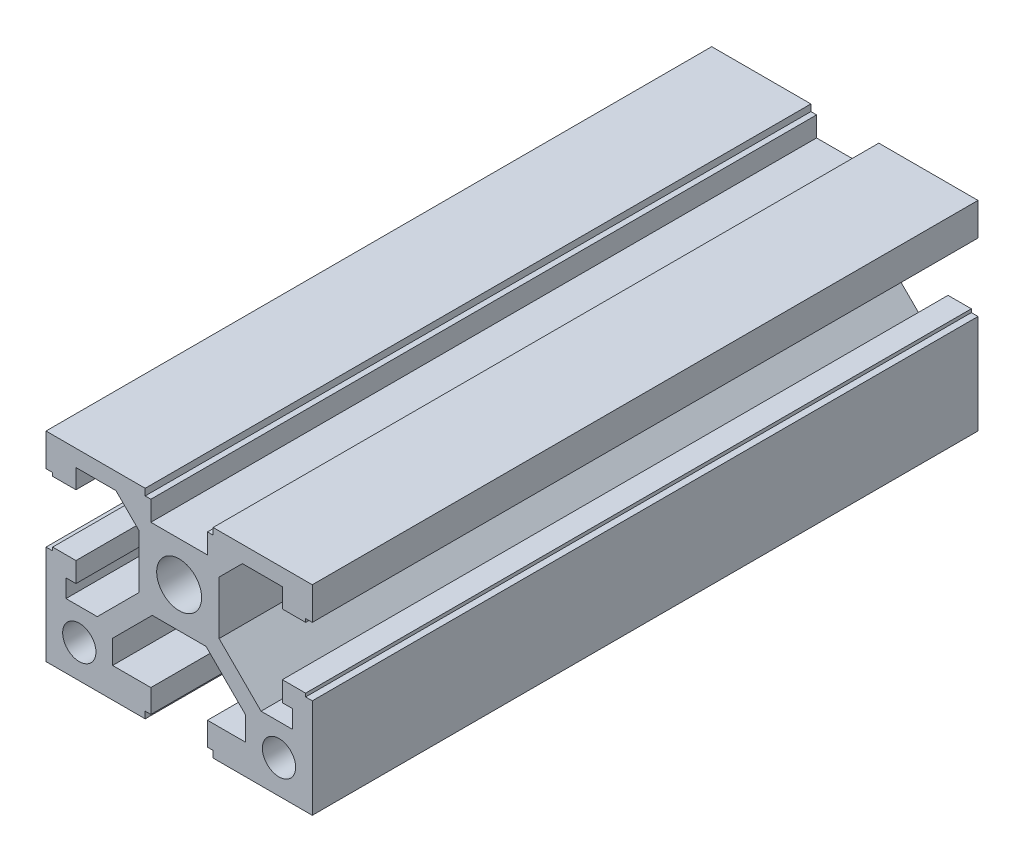
SolidWorks part; units mm, degrees
ref_plane "前视基准面" through (0, 0, 0) normal (0, 0, 1) x (1, 0, 0)
ref_plane "上视基准面" through (0, 0, 0) normal (0, 1, 0) x (1, 0, 0)
ref_plane "右视基准面" through (0, 0, 0) normal (1, 0, 0) x (0, 0, -1)
sketch "草图1" plane through (0, 0, 0) normal (0, 0, 1) x (1, 0, 0)
  line L0 (20, 41.4177) -> (20, -4.8401) construction
  line L1 (0, 0) -> (14.9, 0)
  line L2 (0, 0) -> (0, 14.9)
  line L3 (0, 30) -> (14.9, 30)
  line L4 (40, 0) -> (40, 14.9)
  line L5 (0, 25.1) -> (0, 30)
  line L6 (14.9, 30) -> (14.9, 29)
  line L7 (14.9, 29) -> (15.75, 29)
  line L8 (25.1, 30) -> (25.1, 29)
  line L9 (25.1, 30) -> (40, 30)
  line L10 (15.75, 29) -> (15.75, 26)
  line L11 (15.75, 26) -> (24.25, 26)
  line L12 (24.25, 29) -> (24.25, 26)
  line L13 (-17.1816, 20) -> (59.6344, 20) construction
  line L14 (24.25, 29) -> (25.1, 29)
  line L15 (0, 25.1) -> (1, 25.1)
  line L16 (4.5, 15.4) -> (4.5, 12.4)
  line L17 (0, 14.9) -> (1, 14.9)
  line L18 (1, 25.1) -> (1, 24.6)
  line L19 (1, 24.6) -> (4.5, 24.6)
  line L20 (10.5, 27.5) -> (14, 24)
  line L21 (1, 15.4) -> (4.5, 15.4)
  line L22 (14, 24) -> (14, 16)
  line L23 (4.5, 27.5) -> (10.5, 27.5)
  line L24 (4.5, 27.5) -> (4.5, 24.6)
  line L25 (4.5, 12.4) -> (3, 12.4)
  line L26 (32.3, 9.7) -> (32.3031, 9.7306)
  line L27 (1, 15.4) -> (1, 14.9)
  line L28 (14, 16) -> (7.7, 9.7)
  line L29 (3, 12.4) -> (3, 9.7)
  line L30 (3, 9.7) -> (7.7, 9.7)
  line L31 (7.7, 9.7) -> (7.6969, 9.7306)
  line L32 (37, 9.7) -> (32.3, 9.7)
  line L33 (37, 12.4) -> (37, 9.7)
  line L34 (26, 16) -> (32.3, 9.7)
  line L35 (39, 15.4) -> (39, 14.9)
  line L36 (35.5, 12.4) -> (37, 12.4)
  line L37 (35.5, 27.5) -> (35.5, 24.6)
  line L38 (35.5, 27.5) -> (29.5, 27.5)
  line L39 (26, 24) -> (26, 16)
  line L40 (39, 15.4) -> (35.5, 15.4)
  line L41 (29.5, 27.5) -> (26, 24)
  line L42 (39, 24.6) -> (35.5, 24.6)
  line L43 (39, 25.1) -> (39, 24.6)
  line L44 (40, 14.9) -> (39, 14.9)
  line L45 (35.5, 15.4) -> (35.5, 12.4)
  line L46 (40, 25.1) -> (39, 25.1)
  line L47 (40, 25.1) -> (40, 30)
  line L48 (25.1, 0) -> (40, 0)
  line L49 (30, 8.0402) -> (24.0402, 14)
  line L50 (14.9, 0) -> (14.9, 1)
  line L51 (14.9, 1) -> (15.75, 1)
  line L52 (30, 4.5) -> (30, 8.0402)
  line L53 (15.75, 4.5) -> (10, 4.5)
  line L54 (15.75, 1) -> (15.75, 4.5)
  line L55 (24.25, 1) -> (24.25, 4.5)
  line L56 (24.25, 4.5) -> (30, 4.5)
  line L57 (10, 4.5) -> (10, 8.0402)
  line L58 (10, 8.0402) -> (15.9598, 14)
  line L59 (15.9598, 14) -> (24.0402, 14)
  line L60 (25.1, 1) -> (24.25, 1)
  line L61 (20, 20) -> (5.6867, 5.6867) construction
  line L62 (25.1, 0) -> (25.1, 1)
  circle A0 centre (20, 20) radius 3.375
  circle A1 centre (35, 5) radius 2.5
  circle A2 centre (5, 5) radius 2.5
  dimension "D27" = 6.75
  dimension "D30" = 5
  dimension "D1" = 40
  dimension "D2" = 30
  dimension "D3" = 10.2
  dimension "D4" = 8.5
  dimension "D5" = 10.2
  dimension "D6" = 2.5
  dimension "D7" = 1
  dimension "D8" = 4
  dimension "D9" = 10.2
  dimension "D10" = 1
  dimension "D11" = 4.5
  dimension "D12" = 9.2
  dimension "D13" = 3
  dimension "D14" = 2.7
  dimension "D15" = 3
  dimension "D16" = 8
  dimension "D17" = 14
  dimension "D18" = 10
  dimension "D19" = 6
  dimension "D20" = 45
  dimension "D21" = 8.5
  dimension "D22" = 2.8
  dimension "D23" = 20
  dimension "D24" = 4.5
  dimension "D25" = 1
  dimension "D26" = 14
  dimension "D28" = 5
  dimension "D29" = 5
extrude "凸台-拉伸1" add sketch "草图1" along normal blind 100 contours L62 L48 L4 L44 L35 L40 L45 L36 L33 L32 L34 L39 L41 L38 L37 L42 L43 L46 L47 L9 L8 L14 L12 L11 L10 L7 L6 L3 L5 L15 L18 L19 L24 L23 L20 L22 L28 L30 L29 L25 L16 L21 L27 L17 L2 L1 L50 L51 L54 L53 L57
